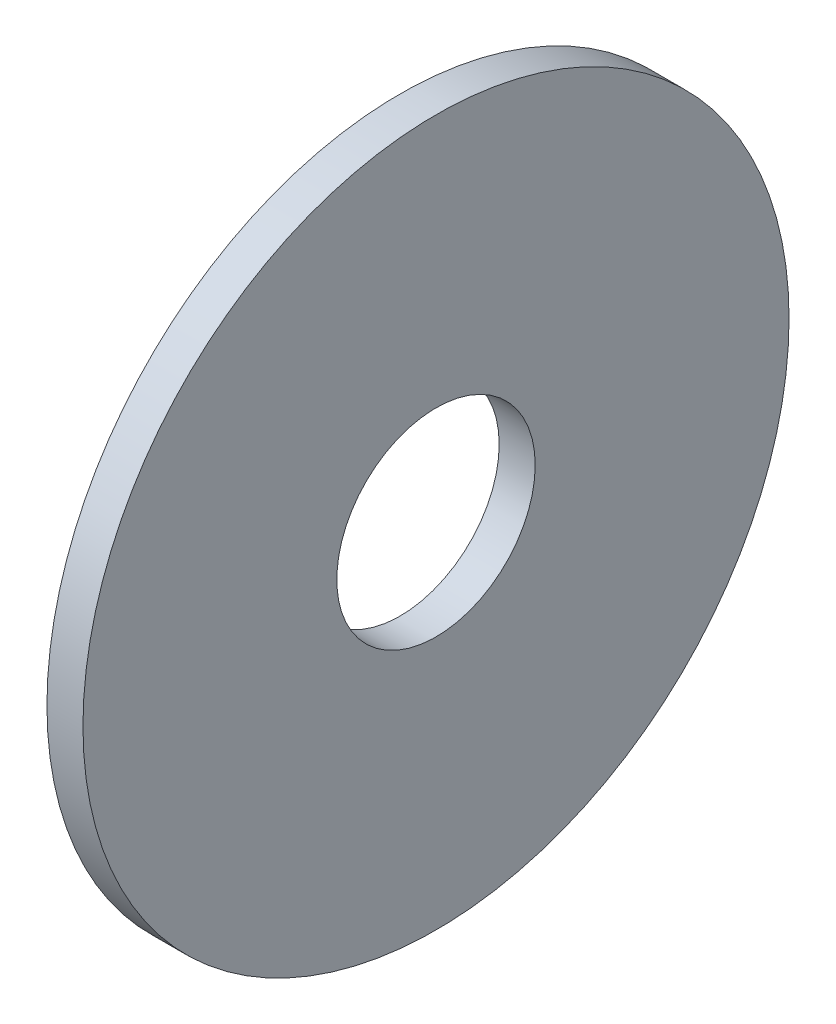
SolidWorks part; units mm, degrees
ref_plane "Front Plane" through (0, 0, 0) normal (0, 0, 1) x (1, 0, 0)
ref_plane "Top Plane" through (0, 0, 0) normal (0, 1, 0) x (1, 0, 0)
ref_plane "Right Plane" through (0, 0, 0) normal (1, 0, 0) x (0, 0, -1)
sketch "Sketch1" plane through (0, 0, 0) normal (1, 0, 0) x (0, 0, -1)
  circle A0 centre (0, 0) radius 12.7
  circle A1 centre (0, 0) radius 3.5687
  dimension "OD" = 25.4
  dimension "ID" = 7.1374
extrude "Boss-Extrude1" add sketch "Sketch1" along normal blind 1.2954
